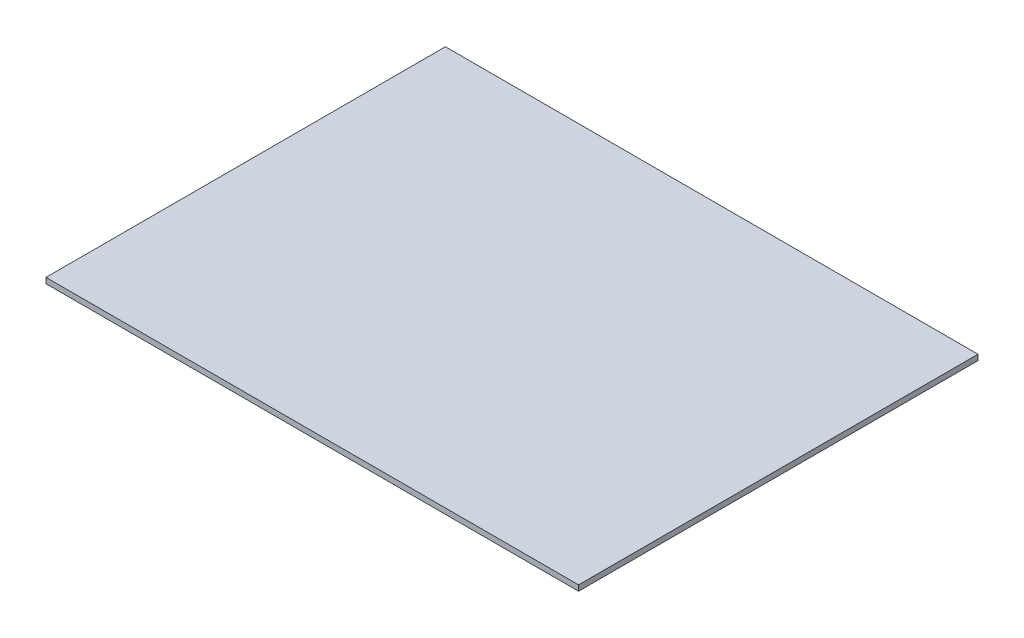
SolidWorks part; units mm, degrees
ref_plane "Front Plane" through (0, 0, 0) normal (0, 0, 1) x (1, 0, 0)
ref_plane "Top Plane" through (0, 0, 0) normal (0, 1, 0) x (1, 0, 0)
ref_plane "Right Plane" through (0, 0, 0) normal (1, 0, 0) x (0, 0, -1)
sketch "Sketch1" plane through (0, 0, 0) normal (0, 1, 0) x (1, 0, 0)
  line L1 (-304.8, -228.6) -> (304.8, -228.6)
  line L2 (-304.8, -228.6) -> (-304.8, 228.6)
  line L3 (-304.8, 228.6) -> (304.8, 228.6)
  line L4 (304.8, -228.6) -> (304.8, 228.6)
  line L5 (-304.8, -228.6) -> (304.8, 228.6) construction
  line L6 (-304.8, 228.6) -> (304.8, -228.6) construction
  point P0 (0, 0)
  dimension "D1" = 609.6
  dimension "D2" = 457.2
extrude "Boss-Extrude1" add sketch "Sketch1" along normal blind 6.35
